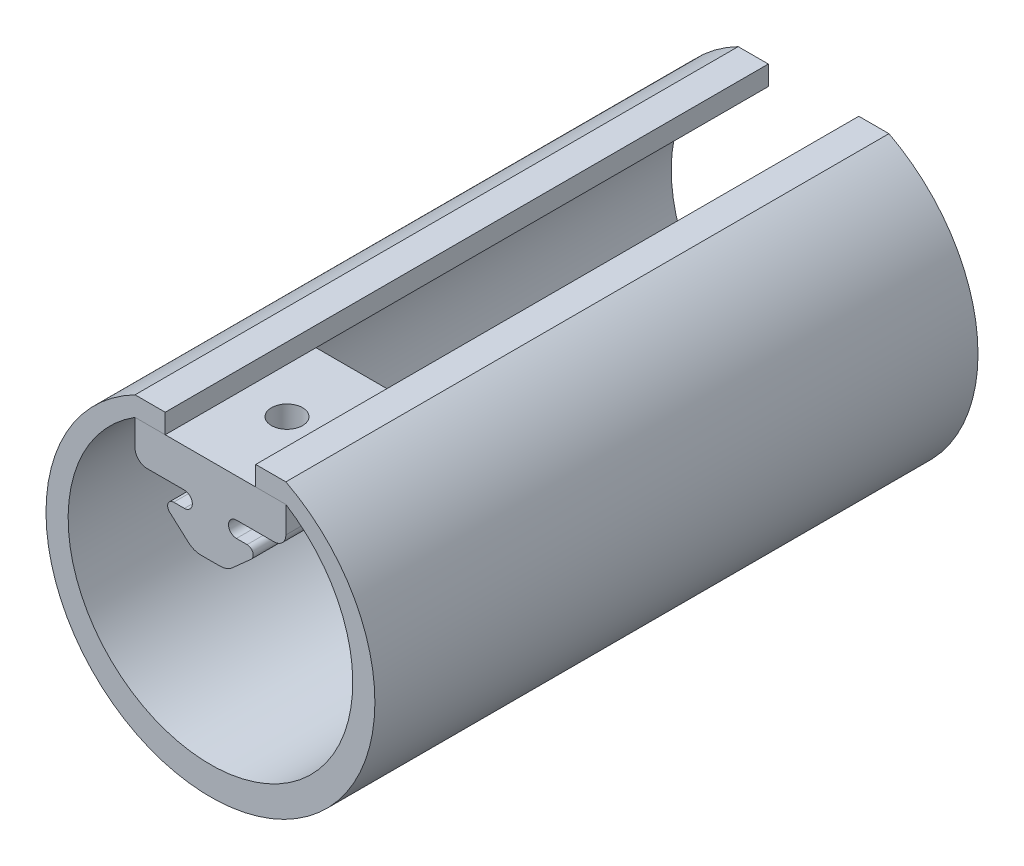
SolidWorks part; units mm, degrees
material "6105-T5 Aluminum"
ref_plane "Front Plane" through (0, 0, 0) normal (0, 0, 1) x (1, 0, 0)
ref_plane "Top Plane" through (0, 0, 0) normal (0, 1, 0) x (1, 0, 0)
ref_plane "Right Plane" through (0, 0, 0) normal (1, 0, 0) x (0, 0, -1)
sketch "Sketch1" plane through (0, 0, 0) normal (0, 0, 1) x (1, 0, 0)
  line L14 (4.315, 12.745) -> (10.5321, 12.745)
  line L15 (12.505, 14.7079) -> (12.505, 19.095)
  line L16 (6.085, 10.115) -> (4.315, 10.115)
  line L17 (3.6646, 5.583) -> (6.7586, 8.3524)
  line L28 (1.5504, 4.775) -> (-1.5504, 4.775)
  line L29 (-3.6646, 5.583) -> (-6.7586, 8.3524)
  line L30 (-6.085, 10.115) -> (-4.315, 10.115)
  line L31 (-12.495, 14.7079) -> (-12.495, 19.095)
  line L32 (-4.315, 12.745) -> (-10.5321, 12.745)
  line L36 (-15.7643, 0) -> (12.505, 0) construction
  line L37 (0, 13.9334) -> (0, -12.3541) construction
  line L38 (-12.495, 19.095) -> (12.505, 19.095)
  arc A12 (4.315, 10.115) -> (4.315, 12.745) centre (4.315, 11.43) cw
  arc A13 (6.085, 10.115) -> (6.7586, 8.3524) centre (6.085, 9.105) cw
  arc A14 (3.6646, 5.583) -> (1.5504, 4.775) centre (1.5504, 7.945) cw
  arc A24 (-3.6646, 5.583) -> (-1.5504, 4.775) centre (-1.5504, 7.945) ccw
  arc A25 (-6.085, 10.115) -> (-6.7586, 8.3524) centre (-6.085, 9.105) ccw
  arc A26 (-4.315, 10.115) -> (-4.315, 12.745) centre (-4.315, 11.43) ccw
  arc A29 (10.5321, 12.745) -> (12.505, 14.7079) centre (10.5421, 14.7079) ccw
  arc A30 (-10.5321, 12.745) -> (-12.495, 14.7079) centre (-10.5321, 14.7079) cw
  dimension "D4" = 14.19
  dimension "D5" = 5.34
  dimension "D6" = 6
  dimension "D7" = 1.01
  dimension "D8" = 6.35
  dimension "D3" = 3.17
  dimension "D2" = 25
  dimension "D10" = 2.63
extrude "Extrude1" add sketch "Sketch1" against normal blind 25
sketch "Sketch2" plane through (0, 19.095, 0) normal (0, 1, 0) x (1, 0, 0)
  line L0 (0, 50.8) -> (0, 0) construction
  line L3 (-12.495, 25) -> (-12.495, 0) construction
  line L4 (-12.495, 12.5) -> (12.5, 12.5) construction
  circle A1 centre (0, 12.7) radius 2.5797
extrude "Cut-Extrude1" cut sketch "Sketch2" against normal through all
sketch "Sketch5" plane through (0, 0, 0) normal (0, 0, 1) x (1, 0, 0)
  line L0 (-12.495, 19.095) -> (-12.495, 22.3324)
  line L1 (-12.495, 22.3324) -> (-7.495, 22.3324)
  line L2 (12.505, 22.3324) -> (12.505, 19.095)
  line L3 (-7.495, 22.3324) -> (-7.495, 19.095)
  line L4 (12.505, 19.095) -> (-12.495, 19.095) construction
  line L5 (7.505, 22.3324) -> (7.505, 19.095)
  line L6 (-12.495, 22.3324) -> (-7.495, 22.3324)
  line L7 (-7.495, 19.095) -> (-12.495, 19.095)
  line L8 (7.505, 22.3324) -> (12.505, 22.3324)
  line L9 (12.505, 19.095) -> (7.505, 19.095)
  line L10 (7.505, 22.3324) -> (12.505, 22.3324)
  arc A0 (-12.495, 19.095) -> (12.505, 19.095) centre (0.005, -0.9197) ccw
  arc A1 (-12.495, 22.3324) -> (12.505, 22.3324) centre (0.005, -1.9007) ccw
  line M3 (12.505, 19.095) -> (-12.495, 19.095)
  dimension "D1" = 5
  dimension "D2" = 5
extrude "Boss-Extrude1" add sketch "Sketch5" against normal blind 100 separate body contours L0 A1 L2 A0 | L3 L1 L0 M3 | L8 L5 L2 M3
